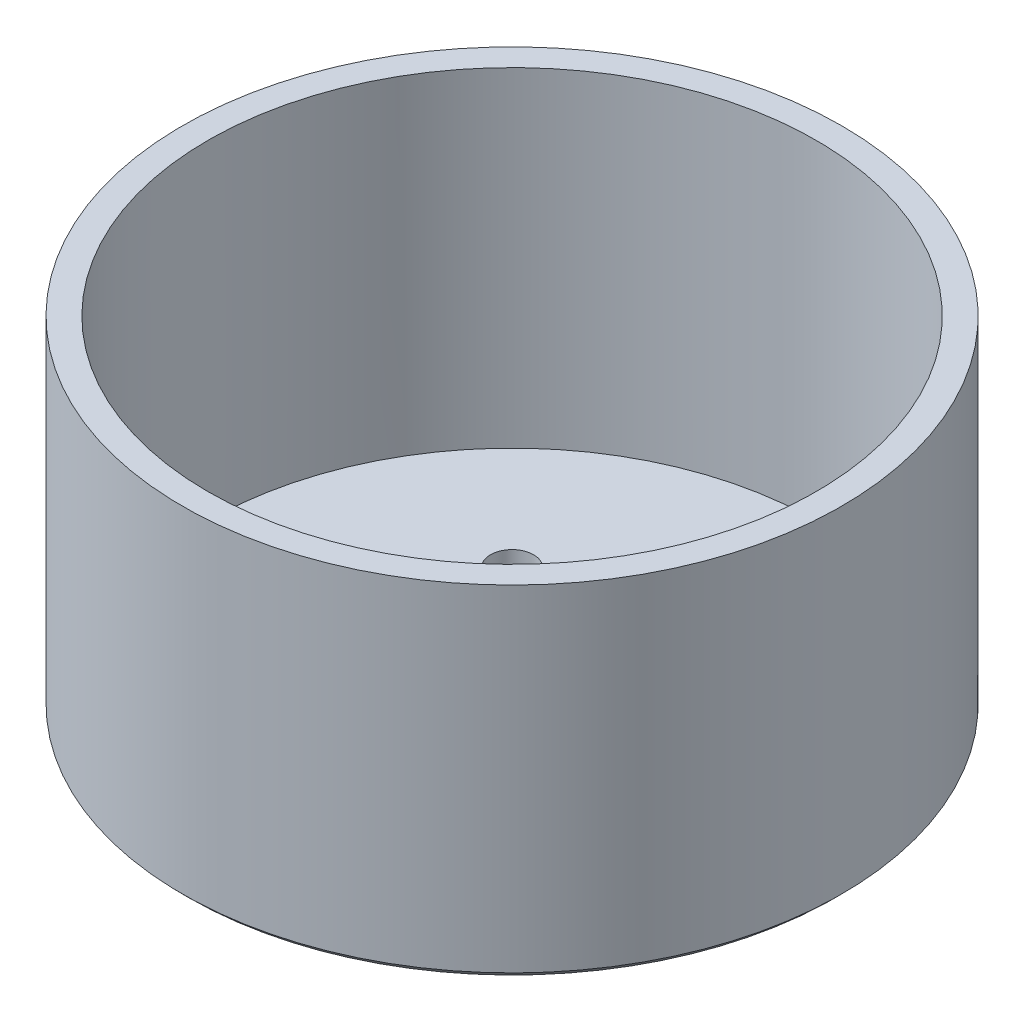
SolidWorks part; units mm, degrees
material "Сплав 2024"
ref_plane "Спереди" through (0, 0, 0) normal (0, 0, 1) x (1, 0, 0)
ref_plane "Сверху" through (0, 0, 0) normal (0, 1, 0) x (1, 0, 0)
ref_plane "Справа" through (0, 0, 0) normal (1, 0, 0) x (0, 0, -1)
sketch "Эскиз1" plane through (0, 0, 0) normal (0, 1, 0) x (1, 0, 0)
  circle A0 centre (0, 0) radius 24
  circle A1 centre (0, 0) radius 26
  dimension "D1" = 48
  dimension "D2" = 2
extrude "Бобышка-Вытянуть1" add sketch "Эскиз1" along normal blind 26
sketch "Эскиз2" plane through (0, 0, 0) normal (0, -1, 0) x (1, 0, 0)
  circle A0 centre (0, 0) radius 26 construction
  circle A1 centre (0, 0) radius 26
extrude "Бобышка-Вытянуть2" add sketch "Эскиз2" along normal blind 1
sketch "Эскиз9" plane through (0, 0, 0) normal (0, 1, 0) x (1, 0, 0)
  line L0 (15, 18.735) -> (15, -18.735)
  circle A0 centre (0, 0) radius 24 construction
  arc A1 (15, -18.735) -> (15, 18.735) centre (0, 0) ccw
  dimension "D1" = 15
extrude "Вырез-Вытянуть4" cut sketch "Эскиз9" against normal up to next
fillet "Скругление2" radius 4 2 edges
sketch "Эскиз3" plane through (0, -1, 0) normal (0, -1, 0) x (1, 0, 0)
  line L0 (15, -6.245) -> (15, 6.245) construction
  line L1 (15, -6.245) -> (15, 6.245)
  arc A0 (19.3647, 10.2283) -> (19.3647, -10.2283) centre (0, 0) ccw
  arc A1 (22.8, 7.494) -> (15, 6.245) centre (19, 6.245) ccw construction
  arc A2 (15, -6.245) -> (22.8, -7.494) centre (19, -6.245) ccw construction
  arc A3 (19.3647, 10.2283) -> (15, 6.245) centre (19, 6.245) ccw
  arc A4 (15, -6.245) -> (19.3647, -10.2283) centre (19, -6.245) ccw
  dimension "D1" = 43.8
extrude "Бобышка-Вытянуть3" add sketch "Эскиз3" along normal blind 0.7
sketch "Эскиз4" plane through (0, -1.7, 0) normal (0, -1, 0) x (1, 0, 0)
  circle A0 centre (0, 0) radius 7
  dimension "D1" = 14
extrude "Вырез-Вытянуть1" cut sketch "Эскиз4" against normal up to next
sketch "Эскиз5" plane through (0, -1.7, 0) normal (0, -1, 0) x (1, 0, 0)
  line L1 (-8.8388, 8.8388) -> (8.8388, 8.8388) construction
  line L2 (-8.8388, 8.8388) -> (-8.8388, -8.8388) construction
  line L3 (-8.8388, -8.8388) -> (8.8388, -8.8388) construction
  line L4 (8.8388, 8.8388) -> (8.8388, -8.8388) construction
  line L5 (-8.8388, 8.8388) -> (8.8388, -8.8388) construction
  line L6 (-8.8388, -8.8388) -> (8.8388, 8.8388) construction
  point P0 (0, 0)
  dimension "D1" = 25
  dimension "D2" = 90
hole_wizard "Отверстие с зазором M31" positions "Эскиз7" profile "Эскиз6" hole size "M3" standard "Ansi Metric" end condition up to next
sketch "Эскиз7" plane through (0, -1.7, 0) normal (0, -1, 0) x (-1, 0, 0)
  point P0 (8.8388, -8.8388)
  point P3 (-8.8388, -8.8388)
  point P6 (-8.8388, 8.8388)
  point P9 (8.8388, 8.8388)
sketch "Эскиз6" plane through (-8.8388, -1.7, 8.8388) normal (1, 0, 0) x (0, 0, -1)
  line L0 (0, 0) -> (0, 1.7)
  line L1 (0, 1.7) -> (1.7, 1.7)
  line L2 (1.7, 1.7) -> (1.7, 0)
  line L5 (1.7, 0) -> (0, 0)
  line L11 (0, -6.35) -> (0, 107.95) construction
  dimension "Диаметр сквозного отверстия" = 3.4
  dimension "Глубина сквозного отверстия" = 1.7
chamfer "Фаска1" distance 0.5 angle 45 1 edges at (0, -1, -26)
